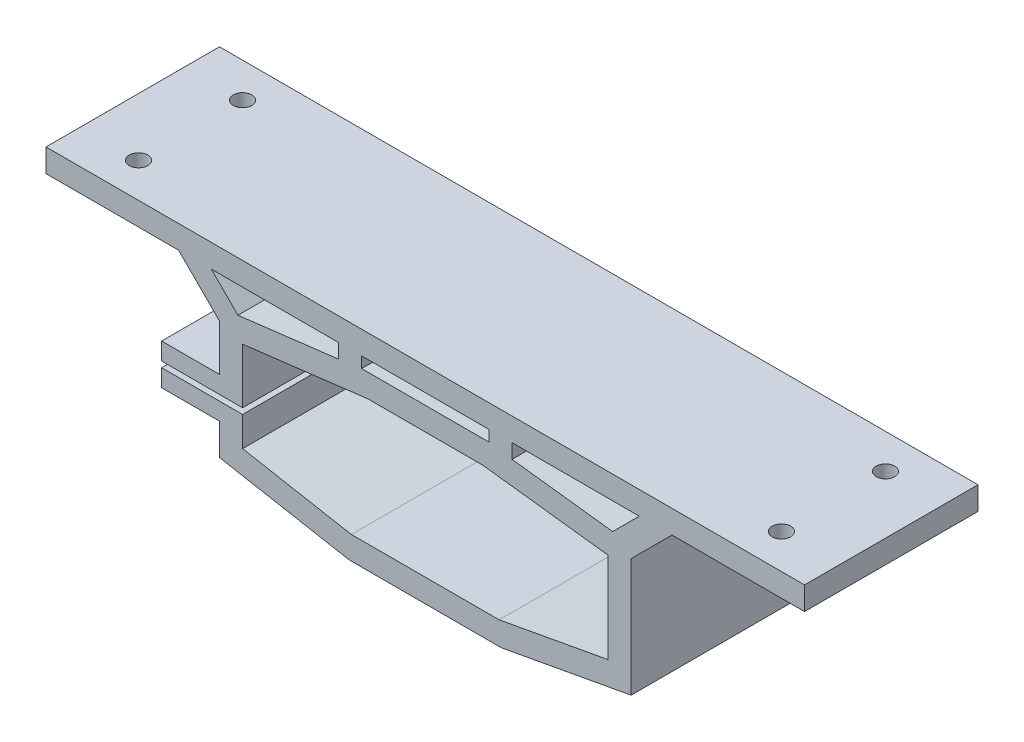
SolidWorks part; units mm, degrees
ref_plane "Front Plane" through (0, 0, 0) normal (0, 0, 1) x (1, 0, 0)
ref_plane "Top Plane" through (0, 0, 0) normal (0, 1, 0) x (1, 0, 0)
ref_plane "Right Plane" through (0, 0, 0) normal (1, 0, 0) x (0, 0, -1)
ref_plane "Plane1" through (0, 0, 70) normal (0, 0, 1) x (1, 0, 0)
sketch "Sketch2" plane through (0, 0, 70) normal (0, 0, 1) x (1, 0, 0)
  line L0 (31.6, 1.9592) -> (31.6, -13.6905)
  line L1 (31.6, -13.6905) -> (12.7818, -17.1405)
  line L2 (12.7818, -17.1405) -> (-12.7818, -17.1405)
  line L3 (-12.7818, -17.1405) -> (-31.6, -13.6905)
  line L4 (-31.6, -13.6905) -> (-31.6, -8.5711)
  line L5 (-31.6, 1.9592) -> (-9.9453, 4.6)
  line L6 (-9.9453, 4.6) -> (9.9453, 4.6)
  line L7 (9.9453, 4.6) -> (31.6, 1.9592)
  line L8 (22.4, 2.9804) -> (23.5, 2.8462) construction
  line L9 (-23.5, 2.8462) -> (-22.4, 2.9804) construction
  line L10 (-12.9528, -17.0075) -> (-29.7865, -13.9213) construction
  line L11 (29.7865, -13.9213) -> (12.9528, -17.0075) construction
  line L12 (-31.6, -7.5711) -> (-45.6, -7.5711)
  line L13 (12.6662, -17.0405) -> (-12.6662, -17.0405) construction
  line L14 (-7, 4.5) -> (-5.9, 4.5) construction
  line L15 (35.6, 3.4289) -> (35.6, -17.0239)
  line L16 (35.6, -17.0239) -> (13.1455, -21.1405)
  line L17 (13.1455, -21.1405) -> (-13.1455, -21.1405)
  line L18 (-13.1455, -21.1405) -> (-35.6, -17.0239)
  line L19 (-35.6, -17.0239) -> (-35.6, -11.5711)
  line L20 (-35.6, -11.5711) -> (-45.6, -11.5711)
  line L21 (-45.6, -11.5711) -> (-45.6, -8.5711)
  line L22 (-45.6, -4.5711) -> (-35.6, -4.5711)
  line L23 (-35.6, -4.5711) -> (-35.6, 3.4289)
  line L24 (-35.6, 3.4289) -> (-42.6711, 10.5)
  line L25 (-42.6711, 10.5) -> (-65.6, 10.5)
  line L26 (-65.6, 10.5) -> (-65.6, 14.5)
  line L27 (-90, 14.5) -> (-26.639, 14.5) construction
  line L28 (-65.6, 14.5) -> (65.6, 14.5)
  line L29 (26.639, 14.5) -> (90, 14.5) construction
  line L30 (65.6, 14.5) -> (65.6, 10.5)
  line L31 (65.6, 10.5) -> (42.6711, 10.5)
  line L32 (42.6711, 10.5) -> (35.6, 3.4289)
  line L33 (37.0142, 10.5) -> (32.4049, 5.8907)
  line L34 (32.4049, 5.8907) -> (15.0142, 8.0115)
  line L35 (15.0142, 8.0115) -> (15.0142, 10.5)
  line L36 (15.0142, 10.5) -> (37.0142, 10.5)
  line L37 (11.0142, 10.5) -> (11.0142, 8.6)
  line L38 (11.0142, 8.6) -> (-11.0142, 8.6)
  line L39 (-11.0142, 8.6) -> (-11.0142, 10.5)
  line L40 (-11.0142, 10.5) -> (11.0142, 10.5)
  line L41 (-15.0142, 10.5) -> (-15.0142, 8.0115)
  line L42 (-15.0142, 8.0115) -> (-32.4049, 5.8907)
  line L43 (-32.4049, 5.8907) -> (-37.0142, 10.5)
  line L44 (-37.0142, 10.5) -> (-15.0142, 10.5)
  line L46 (-45.6, -8.5711) -> (-31.6, -8.5711)
  line L47 (-45.6, -7.5711) -> (-45.6, -4.5711)
  line L48 (-31.6, -7.5711) -> (-31.6, 1.9592)
  point P54 (0, 8.6)
  point P58 (34.7095, 8.1953)
  dimension "D1" = 0.1
  dimension "D2" = 0.1
  dimension "D3" = 0.1
  dimension "D4" = 0.1
  dimension "D5" = 0.1
  dimension "D6" = 0.1
  dimension "D7" = 0.1
  dimension "D8" = 0.1
  dimension "D9" = 135
  dimension "D10" = 135
  dimension "D11" = 4
  dimension "D12" = 4
  dimension "D13" = 4
  dimension "D14" = 4
  dimension "D15" = 4
  dimension "D16" = 4
  dimension "D17" = 4
  dimension "D18" = 4
  dimension "D19" = 4
  dimension "D20" = 4
  dimension "D21" = 4
  dimension "D22" = 4
  dimension "D23" = 4
  dimension "D24" = 4
  dimension "D25" = 30
  dimension "D26" = 30
  dimension "D27" = 10
  dimension "D28" = 10
  dimension "D29" = 22
  dimension "D30" = 1
  dimension "D31" = 3
  dimension "D32" = 3
  dimension "D33" = 10
  dimension "D34" = 8
extrude "Extrude1" add sketch "Sketch2" along normal blind 20 and the other way blind 10
sketch "Sketch3" plane through (0, 10.5, 0) normal (0, -1, 0) x (1, 0, 0)
  line L0 (-65.6, 60) -> (-65.6, 90) construction
  line L1 (-55.6, 84) -> (55.6, 84) construction
  line L2 (-55.6, 84) -> (-55.6, 66) construction
  line L3 (-55.6, 66) -> (55.6, 66) construction
  line L4 (55.6, 84) -> (55.6, 66) construction
  line L5 (65.6, 60) -> (65.6, 90) construction
  line L6 (42.6711, 90) -> (65.6, 90) construction
  line L7 (42.6711, 60) -> (65.6, 60) construction
  circle A0 centre (-55.6, 84) radius 1.6
  circle A1 centre (-55.6, 66) radius 1.6
  circle A2 centre (55.6, 84) radius 1.6
  circle A3 centre (55.6, 66) radius 1.6
  dimension "D5" = 3.2
  dimension "D1" = 10
  dimension "D2" = 10
  dimension "D3" = 6
  dimension "D4" = 6
extrude "Cut-Extrude1" cut sketch "Sketch3" against normal blind 20
sketch "Sketch4" plane through (0, -11.5711, 0) normal (0, -1, 0) x (1, 0, 0)
  line L0 (-45.6, 60) -> (-45.6, 90) construction
  circle A0 centre (-41.6, 75) radius 2.15
  point P4 (-45.6, 75)
  dimension "D1" = 4
  dimension "D2" = 4.3
extrude "Cut-Extrude2" cut sketch "Sketch4" against normal blind 15
